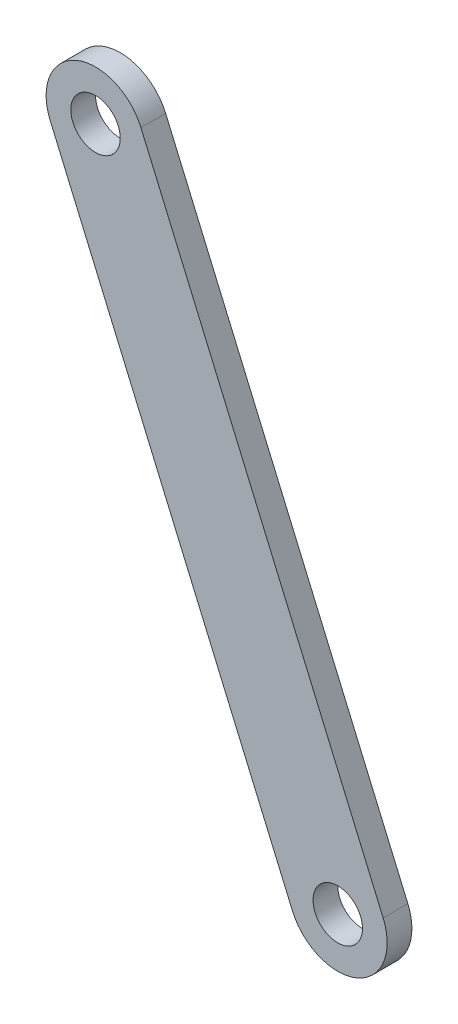
SolidWorks part; units mm, degrees
ref_plane "Front" through (0, 0, 0) normal (0, 0, 1) x (1, 0, 0)
ref_plane "Top" through (0, 0, 0) normal (0, 1, 0) x (1, 0, 0)
ref_plane "Right" through (0, 0, 0) normal (1, 0, 0) x (0, 0, -1)
sketch "Sketch1" plane through (0, 0, 0) normal (0, 0, 1) x (1, 0, 0)
  line L0 (-74.7944, 8.1432) -> (-59.2315, -28.0529) construction
  line L1 (-71.8775, 9.3973) -> (-56.3147, -26.7988)
  line L2 (-77.7112, 6.8891) -> (-62.1483, -29.307)
  arc A0 (-71.8775, 9.3973) -> (-77.7112, 6.8891) centre (-74.7944, 8.1432) ccw
  arc A1 (-62.1483, -29.307) -> (-56.3147, -26.7988) centre (-59.2315, -28.0529) ccw
  circle A2 centre (-59.2315, -28.0529) radius 1.5875
  circle A3 centre (-74.7944, 8.1432) radius 1.5875
  point P4 (-67.0129, -9.9549)
  dimension "D1" = 3.175
  dimension "D2" = 6.35
extrude "Boss-Extrude1" add sketch "Sketch1" along normal blind 1.5875
